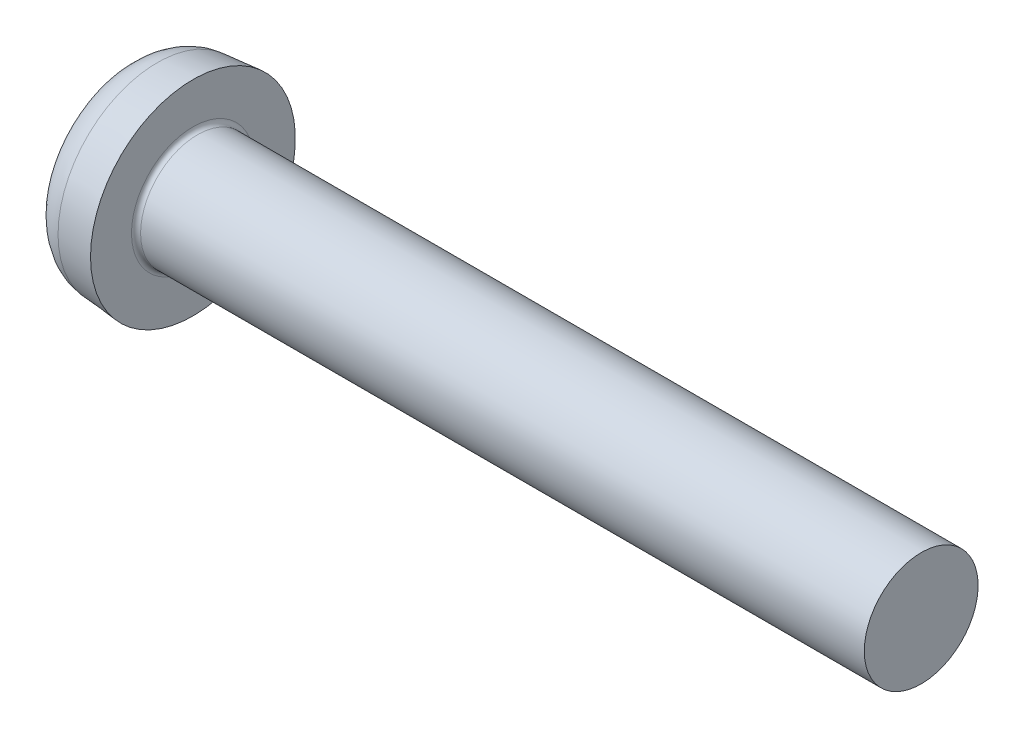
SolidWorks part; units mm, degrees
ref_plane "Front Plane" through (0, 0, 0) normal (0, 0, 1) x (1, 0, 0)
ref_plane "Top Plane" through (0, 0, 0) normal (0, 1, 0) x (1, 0, 0)
ref_plane "Right Plane" through (0, 0, 0) normal (1, 0, 0) x (0, 0, -1)
other "Configuration Table"
sketch "BodySke" plane through (0, 0, 0) normal (0, 0, 1) x (1, 0, 0)
  line L0 (0, 0) -> (111.3824, 0) construction
  line L1 (0, 0) -> (0, 8) construction
  line L2 (1.7, 1.25) -> (1.7, 2.25)
  line L3 (1.7, 2.25) -> (0.918, 2.1816)
  line L4 (1.7, 1.25) -> (17.7, 1.25)
  line L5 (17.7, 1.25) -> (17.7, 0)
  line L6 (2.15, 5.074) -> (2.15, -9.6439) construction
  line L7 (0, 0) -> (17.7, 0)
  line L8 (5.7, 6.074) -> (5.7, -7.708) construction
  arc A0 (0.918, 2.1816) -> (0.2166, 1.5976) centre (0.9877, 1.3846) ccw
  arc A1 (0.2166, 1.5976) -> (0, 0) centre (6, 0) ccw
  point P10 (17.7, 0.9965)
  dimension "Thread_minor" = 1.993
  dimension "Head_side_radius" = 0.8
  dimension "Head_radius" = 6
  dimension "Diameter" = 2.5
  dimension "Thread_length" = 12
  dimension "Head_height" = 1.7
  dimension "Advance" = 0.45
  dimension "Length" = 16
  dimension "D1" = 5
  dimension "Head_dia" = 4.5
revolve "BaseBody" add sketch "BodySke" angle 360 about L0
cosmetic thread "ThreadCosmetic" [suppressed] parameters "Thread_minor"=1.993
fillet "Fillet1" radius 0.1 1 edges at (1.7, 0, 1.25)
ref_plane "Plane1" through (1.42, 0, 0) normal (1, 0, 0) x (0, 0, -1)
sketch "RecSkeTop" plane through (0, 0, 0) normal (1, 0, 0) x (0, 0, -1)
  line L1 (-0.286, 1.3) -> (0.286, 1.3)
  line L2 (-0.286, 1.3) -> (-0.286, -1.3)
  line L3 (-0.286, -1.3) -> (0.286, -1.3)
  line L4 (0.286, 1.3) -> (0.286, -1.3)
  dimension "Cross_dia" = 2.6
  dimension "D1" = 1.3
  dimension "D2" = 0.572
  dimension "D3" = 0.286
sketch "RecSkeBot" plane through (1.42, 0, 0) normal (1, 0, 0) x (0, 0, -1)
  line L0 (-0.286, 1.3) -> (-0.286, -1.3) construction
  line L1 (-0.286, 0.592) -> (0.286, 0.592)
  line L2 (-0.286, 0.592) -> (-0.286, -0.592)
  line L3 (-0.286, -0.592) -> (0.286, -0.592)
  line L4 (0.286, 0.592) -> (0.286, -0.592)
  line L5 (0.286, 1.3) -> (0.286, -1.3) construction
  dimension "D1" = 1.184
  dimension "D2" = 0.592
loft "Recess" cut profiles "RecSkeTop", "RecSkeBot"
pattern_circular "RecPat" count 2 every 90 about axis through (0, 0, 0) along (1, 0, 0) of "Recess"
sketch "RecCorSke" plane through (0, 0, 0) normal (0, 0, 1) x (1, 0, 0)
  line L0 (0, 0) -> (57.5987, 0) construction
  line L1 (0, 0) -> (0, 0.6292)
  line L3 (0, 0.6292) -> (1.42, 0.5299)
  line L4 (1.42, 0.5299) -> (1.5922, 0)
  line L5 (1.5922, 0) -> (0, 0)
  dimension "D1" = 18
  dimension "D2" = 1.42
  dimension "D3" = 0.6292
  dimension "D4" = 4
revolve "RecessCore" cut sketch "RecCorSke" angle 360 about L0
sketch "ThdSchSke" plane through (0, 0, 0) normal (0, 0, 1) x (1, 0, 0)
  line L0 (0, 0) -> (55.1256, 0) construction
  line L1 (0, 0) -> (111.3824, 0) construction
  line L2 (17.5536, 1.25) -> (17.5536, 1.5427)
  line L3 (17.5536, 1.5427) -> (17.8464, 1.5427)
  line L4 (17.8464, 1.5427) -> (17.8464, 1.25)
  line L5 (17.8464, 1.25) -> (17.7, 0.9965)
  line L6 (17.7, 0.9965) -> (17.5536, 1.25)
  line L7 (1.7, 1.25) -> (17.7, 1.25) construction
  line L13 (17.7, 1.25) -> (17.7, 0) construction
revolve "ThreadSchematic" [suppressed] cut sketch "ThdSchSke" angle 360 about L0
pattern_linear "ThdSchPat" [suppressed] count 26 along (1, 0, 0)
equation "\"Thread_minor@ThreadCosmetic\" = \"Thread_minor@BodySke\""
equation "\"D1@RecSkeTop\" = \"Cross_dia@RecSkeTop\" / 2"
equation "\"D2@RecSkeTop\" = \"Cross_dia@RecSkeTop\" * 0.22"
equation "\"D3@RecSkeTop\" = \"D2@RecSkeTop\" / 2"
equation "\"D1@RecSkeBot\" = \"Cross_dia@RecSkeTop\" - 2 * \"Cross_depth@Plane1\" *  tan( 26.5 * 0.017453292 ) "
equation "\"D2@RecSkeBot\" = \"D1@RecSkeBot\" / 2"
equation "\"D2@RecCorSke\" = \"Cross_depth@Plane1\""
equation "\"D3@RecCorSke\" = \"D2@RecSkeTop\" * 1.1"
equation "\"Advance@ThdSchPat\" = \"Advance@BodySke\""
equation "\"D1@ThdSchPat\" =  int( \"Thread_length@BodySke\" / \"Advance@ThdSchPat\" ) "
